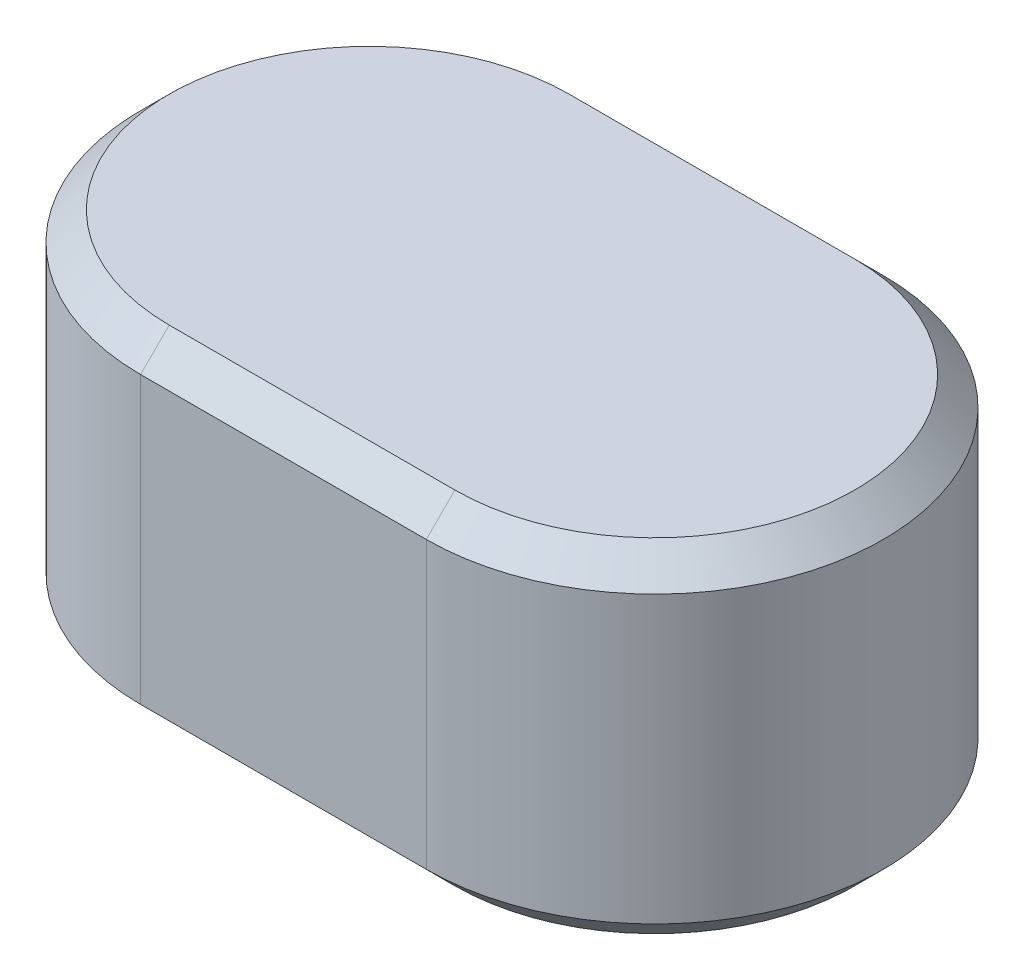
SolidWorks part; units mm, degrees
ref_plane "Piano frontale" through (0, 0, 0) normal (0, 0, 1) x (1, 0, 0)
ref_plane "Piano superiore" through (0, 0, 0) normal (0, 1, 0) x (1, 0, 0)
ref_plane "Piano destro" through (0, 0, 0) normal (1, 0, 0) x (0, 0, -1)
sketch "Schizzo1" plane through (0, 0, 0) normal (0, 1, 0) x (1, 0, 0)
  line L0 (-2.5, 0) -> (2.5, 0) construction
  line L1 (-2.5, 4) -> (2.5, 4)
  line L2 (-2.5, -4) -> (2.5, -4)
  arc A0 (-2.5, 4) -> (-2.5, -4) centre (-2.5, 0) ccw
  arc A1 (2.5, -4) -> (2.5, 4) centre (2.5, 0) ccw
  point P2 (0, 0)
  dimension "D1" = 5
  dimension "D2" = 8
extrude "Estrusione-Estrusione1" add sketch "Schizzo1" along normal blind 6
chamfer "Smusso1" distance 0.5 angle 45 8 edges at (0, 0, 4) (6.5, 0, 0) (0, 0, -4) (-6.5, 0, 0) (0, 6, -4) (6.5, 6, 0) (0, 6, 4) (-6.5, 6, 0)
